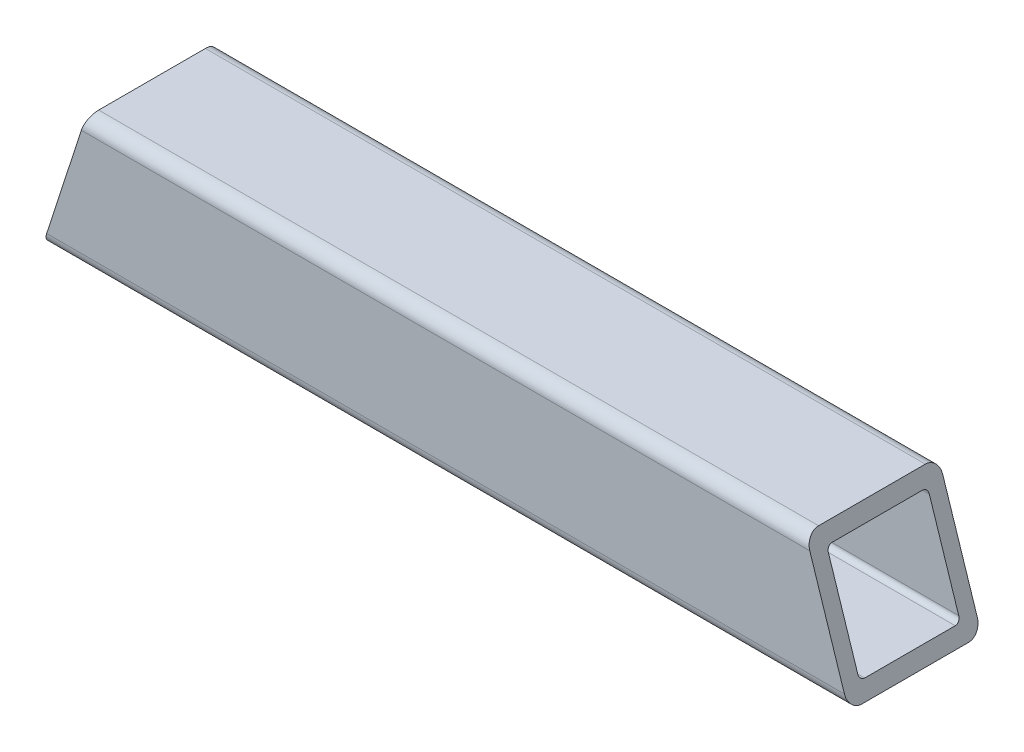
SolidWorks part; units mm, degrees
ref_plane "Front Plane" through (0, 0, 0) normal (0, 0, 1) x (1, 0, 0)
ref_plane "Top Plane" through (0, 0, 0) normal (0, 1, 0) x (1, 0, 0)
ref_plane "Right Plane" through (0, 0, 0) normal (1, 0, 0) x (0, 0, -1)
sketch "Sketch3" plane through (0, 0, 0) normal (1, 0, 0) x (0, 0, -1)
  line L1 (-12.7, 12.7) -> (12.7, 12.7)
  line L2 (-12.7, 12.7) -> (-12.7, -12.7)
  line L3 (-12.7, -12.7) -> (12.7, -12.7)
  line L4 (12.7, 12.7) -> (12.7, -12.7)
  line L5 (-12.7, 12.7) -> (12.7, -12.7) construction
  line L6 (-12.7, -12.7) -> (12.7, 12.7) construction
  line L7 (-9.652, -9.652) -> (9.652, -9.652)
  line L8 (-9.652, -9.652) -> (-9.652, 9.652)
  line L9 (-9.652, 9.652) -> (9.652, 9.652)
  line L10 (9.652, -9.652) -> (9.652, 9.652)
  line L11 (-9.652, -9.652) -> (9.652, 9.652) construction
  line L12 (-9.652, 9.652) -> (9.652, -9.652) construction
  point P0 (0, 0)
  point P6 (0, 0)
  dimension "D1" = 25.4
  dimension "D2" = 19.304
  dimension "D3" = 19.304
  dimension "D4" = 25.4
extrude "Boss-Extrude1" add sketch "Sketch3" against normal blind 154.14
fillet "Fillet1" radius 2.5 4 edges at (-77.07, -12.7, -12.7) (-77.07, -12.7, 12.7) (-77.07, 12.7, -12.7) (-77.07, 12.7, 12.7)
fillet "Fillet2" radius 1 4 edges at (-77.07, -9.652, -9.652) (-77.07, 9.652, -9.652) (-77.07, 9.652, 9.652) (-77.07, -9.652, 9.652)
sketch "Sketch5" plane through (0, 0, -12.7) normal (0, 0, -1) x (-1, 0, 0)
  line L0 (145.7306, 12.7) -> (154.14, 12.7)
  line L2 (154.14, 12.7) -> (145.887, 12.7)
  line L3 (154.14, -12.7) -> (154.14, 12.7)
  line L4 (0, 12.7) -> (8.253, 12.7)
  line L5 (154.14, 12.7) -> (0, 12.7) construction
  line L6 (8.253, 12.7) -> (0, -12.7)
  line L7 (0, -12.7) -> (0, 12.7)
  line L8 (154.14, -12.7) -> (145.887, 12.7)
  line M3 (0, 10.2) -> (0, -10.2)
  line M4 (0, -10.2) -> (154.14, -10.2)
  line M5 (154.14, -10.2) -> (154.14, 10.2)
  line M6 (154.14, 10.2) -> (0, 10.2)
  dimension "D1" = 18
  dimension "D2" = 18
extrude "Cut-Extrude2" cut sketch "Sketch5" against normal through all contours L7 L6 L4 M6 | L6 M6 M3 M4 | L7 L6 M4 | L8 M4 M5 M6 | L8 L3 M4 | L8 L3 L0 M6
